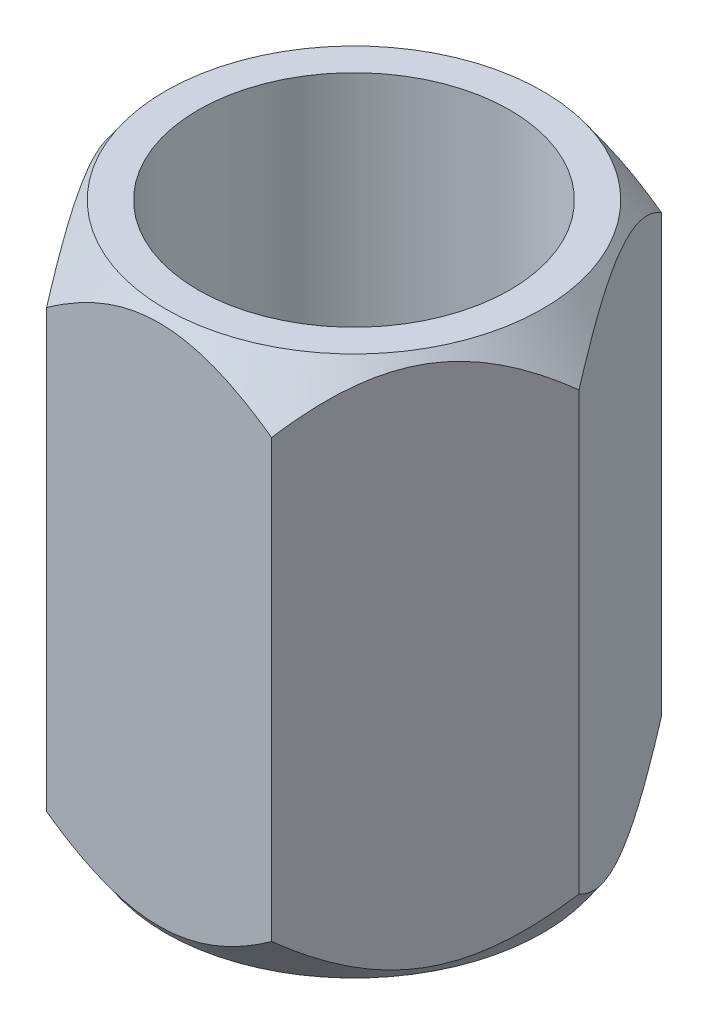
SolidWorks part; units mm, degrees
ref_plane "前视基准面" through (0, 0, 0) normal (0, 0, 1) x (1, 0, 0)
ref_plane "上视基准面" through (0, 0, 0) normal (0, 1, 0) x (1, 0, 0)
ref_plane "右视基准面" through (0, 0, 0) normal (1, 0, 0) x (0, 0, -1)
sketch "草图1" plane through (0, 0, 0) normal (0, 1, 0) x (1, 0, 0)
  line L0 (0, 22.1513) -> (0, -22.1513) construction
  line L2 (4.3301, 7.5) -> (-4.3301, 7.5)
  line L3 (-4.3301, 7.5) -> (-8.6603, 0)
  line L4 (-8.6603, 0) -> (-4.3301, -7.5)
  line L5 (-4.3301, -7.5) -> (4.3301, -7.5)
  line L6 (4.3301, -7.5) -> (8.6603, 0)
  line L7 (8.6603, 0) -> (4.3301, 7.5)
  circle A0 centre (0, 0) radius 6
  circle A1 centre (0, 0) radius 7.5 construction
  point P4 (0, 0)
  dimension "D1" = 12
  dimension "D2" = 15
extrude "凸台-拉伸1" add sketch "草图1" along normal mid plane 20.8
sketch "草图2" plane through (0, 10.4, 0) normal (0, 1, 0) x (1, 0, 0)
  circle A0 centre (0, 0) radius 6.4168
extrude "切除-拉伸1" [suppressed] cut sketch "草图2" against normal blind 8 draft 3
mirror "镜向1" [suppressed] about plane through (0, 0, 0) normal (0, 1, 0)
sketch "草图3" plane through (0, 0, 0) normal (0, 0, 1) x (1, 0, 0)
  line L0 (7.2603, 10.4) -> (8.6603, 8.4)
  line L1 (4.3301, 10.4) -> (8.6603, 10.4) construction
  line L2 (8.6603, 10.4) -> (8.6603, -10.4) construction
  line L3 (8.6603, 8.4) -> (8.6603, 10.4)
  line L4 (8.6603, 10.4) -> (7.2603, 10.4)
  line L5 (0, 21.4439) -> (0, -21.4439) construction
  line L6 (0, 0) -> (15.1843, 0) construction
  line L7 (8.6603, -10.4) -> (7.2603, -10.4)
  line L8 (8.6603, -8.4) -> (8.6603, -10.4)
  line L9 (7.2603, -10.4) -> (8.6603, -8.4)
  point P12 (0, 0)
  dimension "D1" = 1.4
  dimension "D2" = 2
revolve "切除-旋转1" cut sketch "草图3" angle 360 about L5
